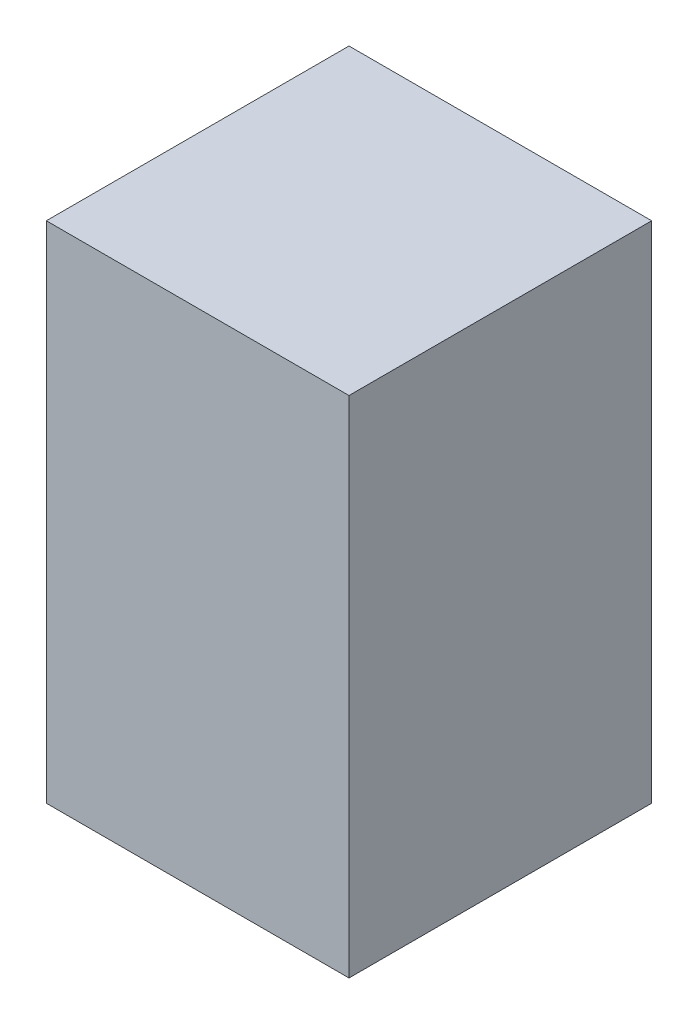
SolidWorks part; units mm, degrees
ref_plane "Front Plane" through (0, 0, 0) normal (0, 0, 1) x (1, 0, 0)
ref_plane "Top Plane" through (0, 0, 0) normal (0, 1, 0) x (1, 0, 0)
ref_plane "Right Plane" through (0, 0, 0) normal (1, 0, 0) x (0, 0, -1)
sketch "Sketch1" plane through (0, 0, 0) normal (0, 0, 1) x (1, 0, 0)
  line L1 (-30, -50) -> (30, -50)
  line L2 (-30, -50) -> (-30, 50)
  line L3 (-30, 50) -> (30, 50)
  line L4 (30, -50) -> (30, 50)
  line L5 (-30, -50) -> (30, 50) construction
  line L6 (-30, 50) -> (30, -50) construction
  point P0 (0, 0)
  dimension "D1" = 100
  dimension "D2" = 60
extrude "Boss-Extrude1" add sketch "Sketch1" along normal mid plane 60
